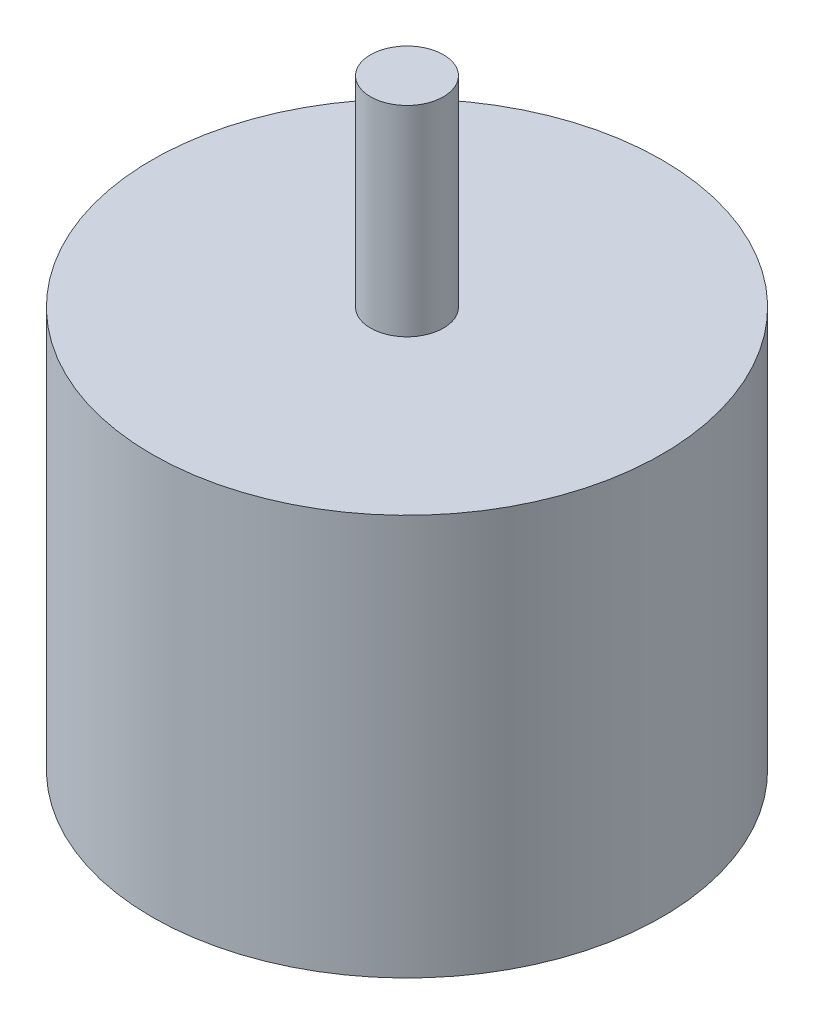
SolidWorks part; units mm, degrees
ref_plane "Front Plane" through (0, 0, 0) normal (0, 0, 1) x (1, 0, 0)
ref_plane "Top Plane" through (0, 0, 0) normal (0, 1, 0) x (1, 0, 0)
ref_plane "Right Plane" through (0, 0, 0) normal (1, 0, 0) x (0, 0, -1)
sketch "Sketch1" plane through (0, 0, 0) normal (0, 1, 0) x (1, 0, 0)
  circle A0 centre (0, 0) radius 22.225
  dimension "D1" = 44.45
extrude "Boss-Extrude1" add sketch "Sketch1" along normal blind 34.925
sketch "Sketch2" plane through (0, 34.925, 0) normal (0, 1, 0) x (1, 0, 0)
  circle A0 centre (0, 0) radius 3.175
extrude "Boss-Extrude2" add sketch "Sketch2" along normal blind 17.4625
